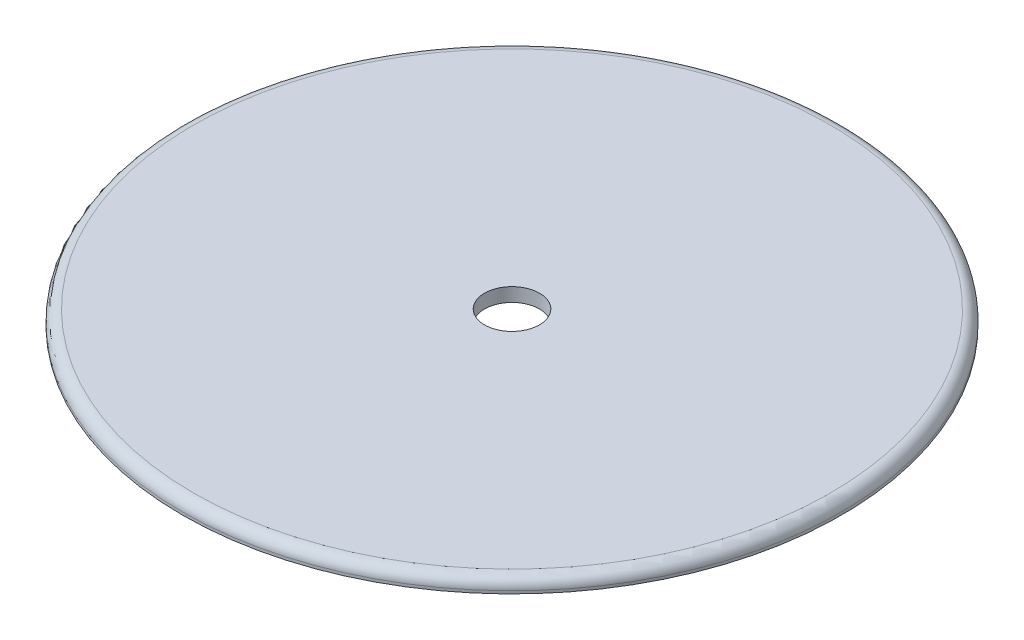
SolidWorks part; units mm, degrees
ref_plane "Front Plane" through (0, 0, 0) normal (0, 0, 1) x (1, 0, 0)
ref_plane "Top Plane" through (0, 0, 0) normal (0, 1, 0) x (1, 0, 0)
ref_plane "Right Plane" through (0, 0, 0) normal (1, 0, 0) x (0, 0, -1)
sketch "Sketch1" plane through (0, 0, 0) normal (0, 1, 0) x (1, 0, 0)
  circle A0 centre (0, 0) radius 38.1
  dimension "D1" = 76.2
extrude "Boss-Extrude1" add sketch "Sketch1" along normal blind 1.5875
fillet "Fillet1" radius 1.27 1 edges at (0, 1.5875, 38.1)
sketch "Sketch2" plane through (0, 0, 0) normal (0, -1, 0) x (1, 0, 0)
  circle A0 centre (0, 0) radius 3.175
  dimension "D1" = 6.35
extrude "Cut-Extrude1" cut sketch "Sketch2" against normal through all
